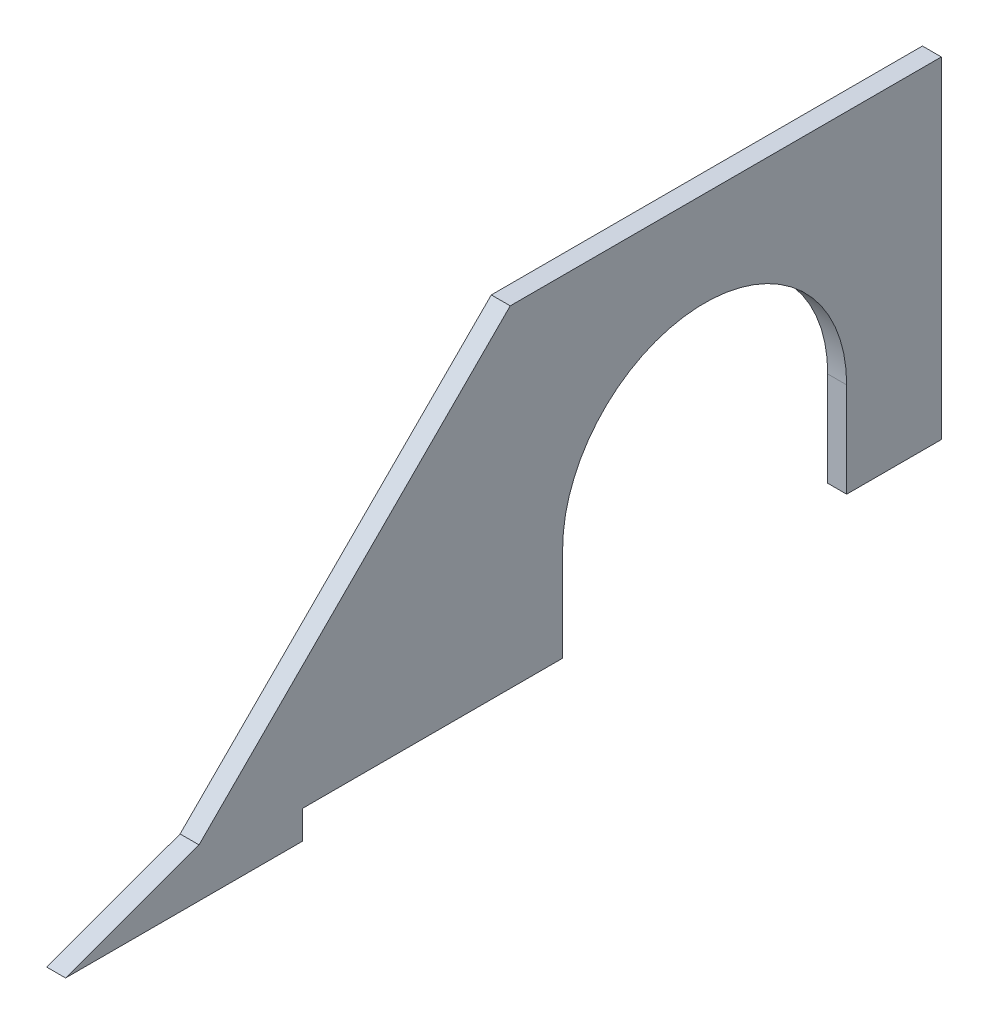
SolidWorks part; units mm, degrees
ref_plane "Alzado" through (0, 0, 0) normal (0, 0, 1) x (1, 0, 0)
ref_plane "Planta" through (0, 0, 0) normal (0, 1, 0) x (1, 0, 0)
ref_plane "Vista lateral" through (0, 0, 0) normal (1, 0, 0) x (0, 0, -1)
sketch "Croquis1" plane through (0, 0, 0) normal (1, 0, 0) x (0, 0, -1)
  line L0 (0, 0) -> (28.1908, 10.2606)
  line L2 (50, 0) -> (0, 0)
  line L4 (50, 0) -> (50, 6)
  line L5 (50, 6) -> (185, 6)
  line L6 (185, 6) -> (185, 76)
  line L7 (185, 76) -> (93.9302, 76)
  line L8 (93.9302, 76) -> (28.1908, 10.2606)
  point P8 (0, 0)
  point P10 (54.7821, 0)
  point P11 (-9.9261, 0)
  dimension "D1" = 20
  dimension "D2" = 50
  dimension "D3" = 135
  dimension "D4" = 6
  dimension "D5" = 45
  dimension "D6" = 70
  dimension "D7" = 30
extrude "Saliente-Extruir2" add sketch "Croquis1" along normal blind 4
sketch "Croquis2" plane through (4, 0, 0) normal (1, 0, 0) x (0, 0, -1)
  line L0 (135, 6) -> (135, 63.4974) construction
  line L1 (50, 6) -> (185, 6) construction
  line L2 (185, 6) -> (185, 76) construction
  line L8 (105, 6) -> (165, 6)
  line L9 (105, 6) -> (105, 26)
  line L11 (165, 6) -> (165, 26)
  arc A2 (165, 26) -> (105, 26) centre (135, 26) ccw
  dimension "D2" = 30
  dimension "D3" = 60
  dimension "D4" = 20
  dimension "D1" = 50
extrude "Cortar-Extruir1" cut sketch "Croquis2" against normal blind 4
